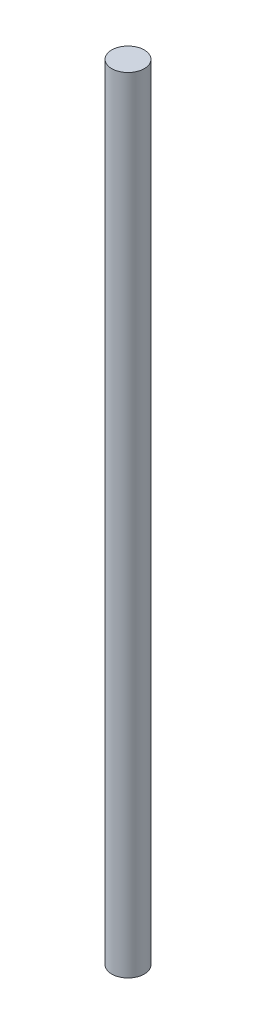
SolidWorks part; units mm, degrees
ref_plane "Front Plane" through (0, 0, 0) normal (0, 0, 1) x (1, 0, 0)
ref_plane "Top Plane" through (0, 0, 0) normal (0, 1, 0) x (1, 0, 0)
ref_plane "Right Plane" through (0, 0, 0) normal (1, 0, 0) x (0, 0, -1)
sketch "Sketch1" plane through (0, 0, 0) normal (0, 1, 0) x (1, 0, 0)
  circle A0 centre (0, 0) radius 6.2
  dimension "D1" = 12.4
extrude "Boss-Extrude1" add sketch "Sketch1" along normal blind 299.5 contours A0
sketch "Sketch2" plane through (0, 0, 0) normal (0, 0, 1) x (1, 0, 0)
  line L0 (6.2, 0) -> (-6.2, 7.1591)
  line L1 (-6.2, 299.5) -> (-6.2, 0) construction
  line L2 (-6.2, 7.1591) -> (-6.2, -10.4862)
  line L3 (-6.2, -10.4862) -> (6.2, -10.4862)
  line L4 (6.2, -10.4862) -> (6.2, 0)
  line L9 (6.2, 0) -> (6.2, 299.5) construction
  line L10 (-6.2, 299.5) -> (6.2, 292.3409)
  line L11 (6.2, 292.3409) -> (6.2, 313.4716)
  line L12 (6.2, 313.4716) -> (-6.2, 313.4716)
  line L13 (-6.2, 313.4716) -> (-6.2, 299.5)
  dimension "D1" = 60
extrude "Cut-Extrude1" [suppressed] cut sketch "Sketch2" against normal through all both and the other way through all
